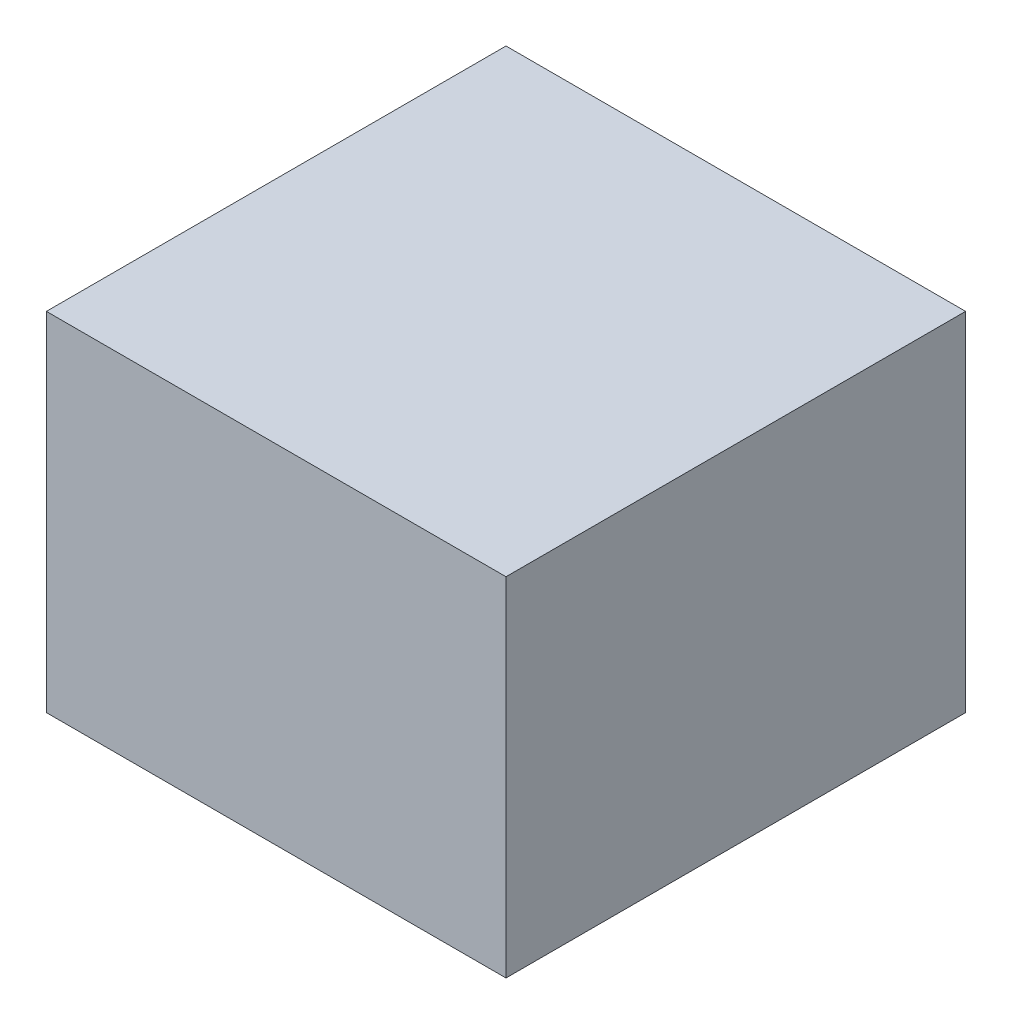
SolidWorks part; units mm, degrees
ref_plane "정면" through (0, 0, 0) normal (0, 0, 1) x (1, 0, 0)
ref_plane "윗면" through (0, 0, 0) normal (0, 1, 0) x (1, 0, 0)
ref_plane "우측면" through (0, 0, 0) normal (1, 0, 0) x (0, 0, -1)
sketch "스케치1" plane through (0, 0, 0) normal (0, 1, 0) x (1, 0, 0)
  line L1 (-41, 41) -> (41, 41)
  line L2 (-41, 41) -> (-41, -41)
  line L3 (-41, -41) -> (41, -41)
  line L4 (41, 41) -> (41, -41)
  line L5 (-41, 41) -> (41, -41) construction
  line L6 (-41, -41) -> (41, 41) construction
  point P0 (0, 0)
  dimension "D1" = 82
  dimension "D2" = 82
extrude "보스-돌출1" add sketch "스케치1" along normal blind 62
